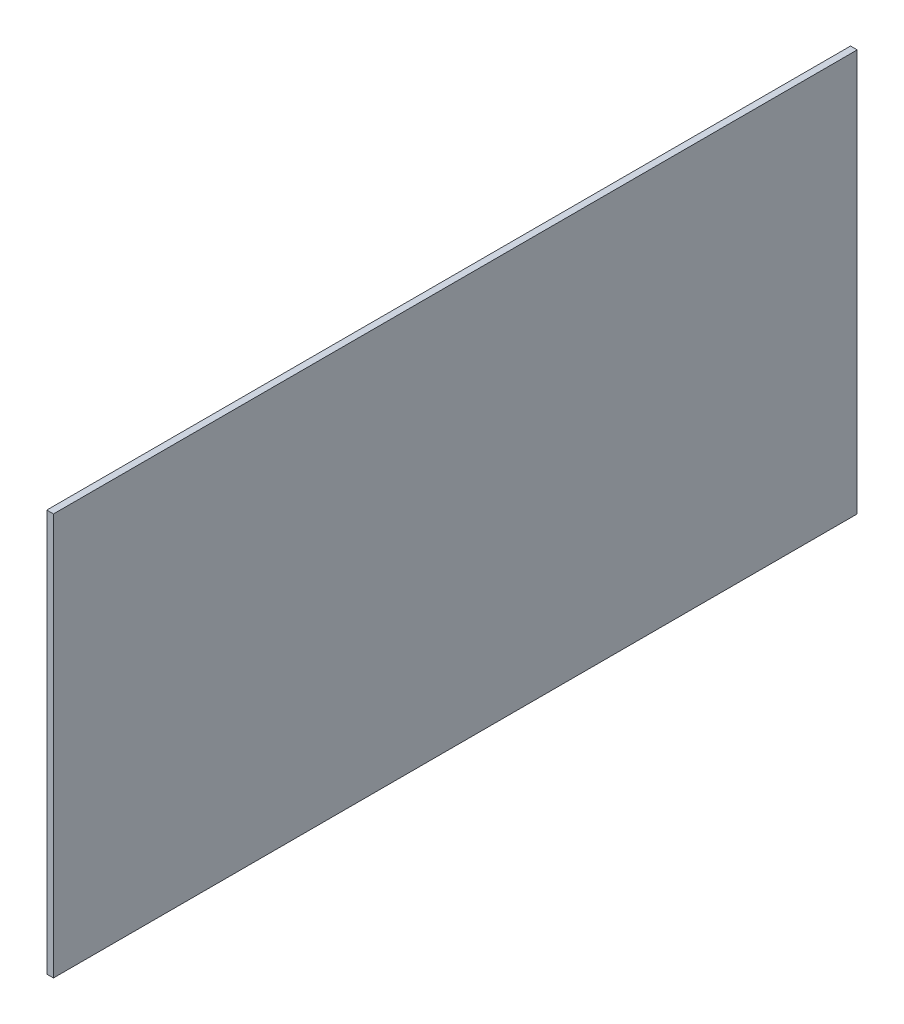
SolidWorks part; units mm, degrees
material "Acero aleado fundido"
ref_plane "Alzado" through (0, 0, 0) normal (0, 0, 1) x (1, 0, 0)
ref_plane "Planta" through (0, 0, 0) normal (0, 1, 0) x (1, 0, 0)
ref_plane "Vista lateral" through (0, 0, 0) normal (1, 0, 0) x (0, 0, -1)
sketch "Croquis1" plane through (0, 0, 0) normal (1, 0, 0) x (0, 0, -1)
  line L1 (300, -150) -> (-300, -150)
  line L2 (300, -150) -> (300, 150)
  line L3 (300, 150) -> (-300, 150)
  line L4 (-300, -150) -> (-300, 150)
  line L5 (300, -150) -> (-300, 150) construction
  line L6 (300, 150) -> (-300, -150) construction
  point P0 (0, 0)
  dimension "D1" = 300
  dimension "D2" = 600
extrude "Saliente-Extruir1" add sketch "Croquis1" along normal blind 5
